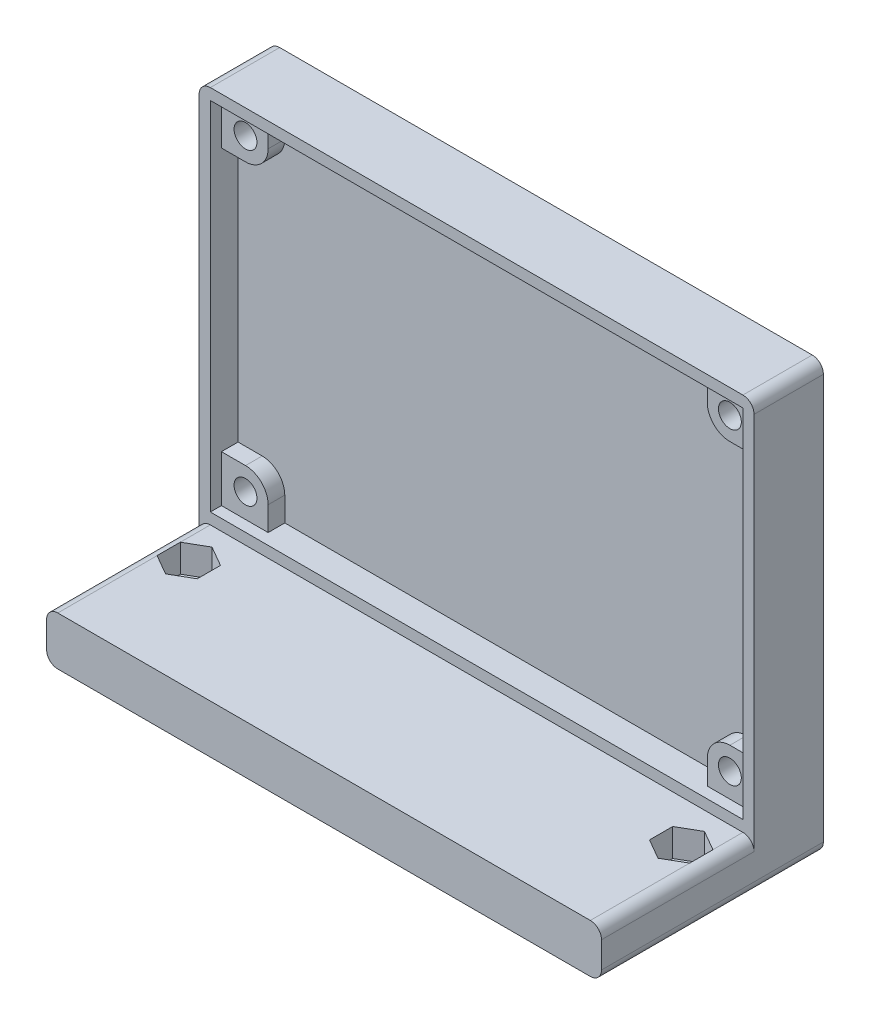
SolidWorks part; units mm, degrees
ref_plane "Front Plane" through (0, 0, 0) normal (0, 0, 1) x (1, 0, 0)
ref_plane "Top Plane" through (0, 0, 0) normal (0, 1, 0) x (1, 0, 0)
ref_plane "Right Plane" through (0, 0, 0) normal (1, 0, 0) x (0, 0, -1)
sketch "Sketch1" plane through (0, 0, 0) normal (0, 0, 1) x (1, 0, 0)
  line L23 (-40.01, -32.7) -> (-40.01, 25.7)
  line L25 (40.01, 25.7) -> (40.01, -32.7)
  line L30 (-38.4, -34.31) -> (38.4, -34.31)
  line L32 (-38.4, 27.31) -> (38.4, 27.31)
  circle A0 centre (-34.925, 22.225) radius 1.65
  circle A1 centre (-34.925, -22.225) radius 1.65
  circle A2 centre (34.925, 22.225) radius 1.65
  circle A3 centre (34.925, -22.225) radius 1.65
  arc A8 (-38.4, 27.31) -> (-40.01, 25.7) centre (-38.4, 25.7) ccw
  arc A9 (40.01, 25.7) -> (38.4, 27.31) centre (38.4, 25.7) ccw
  arc A10 (38.4, -34.31) -> (40.01, -32.7) centre (38.4, -32.7) ccw
  arc A11 (-40.01, -32.7) -> (-38.4, -34.31) centre (-38.4, -32.7) ccw
extrude "Boss-Extrude1" add sketch "Sketch1" along normal blind 32
sketch "Sketch4" plane through (0, 0, 32) normal (0, 0, 1) x (1, 0, 0)
  line L0 (-38.4, -27.31) -> (38.4, -27.31)
  line L1 (-40.01, -28.92) -> (-40.01, 25.7)
  line L2 (-38.4, 27.31) -> (38.4, 27.31)
  line L5 (40.01, -28.92) -> (40.01, 25.7)
  arc A0 (-38.4, 27.31) -> (-40.01, 25.7) centre (-38.4, 25.7) ccw
  arc A1 (40.01, 25.7) -> (38.4, 27.31) centre (38.4, 25.7) ccw
  arc A2 (-38.4, -27.31) -> (-40.01, -28.92) centre (-38.4, -28.92) ccw
  arc A3 (40.01, -28.92) -> (38.4, -27.31) centre (38.4, -28.92) ccw
extrude "Cut-Extrude3" cut sketch "Sketch4" against normal offset from surface (22 mm away) 10 up to face at (0, -3.5, 0)
sketch "Sketch2" plane through (0, 0, 32) normal (0, 0, 1) x (1, 0, 0)
  line L0 (-31.665, 25.7) -> (31.665, 25.7)
  line L1 (-38.4, 18.965) -> (-38.4, -18.965)
  line L2 (-31.665, -25.7) -> (31.665, -25.7)
  line L3 (38.4, 18.965) -> (38.4, -18.965)
  line L5 (-38.4, 18.965) -> (-34.925, 18.965)
  line L14 (-31.665, 25.7) -> (-31.665, 22.225)
  line L15 (31.665, 25.7) -> (31.665, 22.225)
  line L17 (34.925, 18.965) -> (38.4, 18.965)
  line L19 (38.4, -18.965) -> (34.925, -18.965)
  line L20 (31.665, -22.225) -> (31.665, -25.7)
  line L21 (-31.665, -22.225) -> (-31.665, -25.7)
  line L22 (-34.925, -18.965) -> (-38.4, -18.965)
  arc A0 (-34.925, 18.965) -> (-31.665, 22.225) centre (-34.925, 22.225) ccw
  arc A1 (34.925, 18.965) -> (31.665, 22.225) centre (34.925, 22.225) cw
  arc A2 (34.925, -18.965) -> (31.665, -22.225) centre (34.925, -22.225) ccw
  arc A3 (-34.925, -18.965) -> (-31.665, -22.225) centre (-34.925, -22.225) cw
extrude "Cut-Extrude1" cut sketch "Sketch2" against normal offset from surface (26 mm away) 6 up to face at (0, -3.5, 0)
sketch "Sketch3" plane through (0, 0, 32) normal (0, 0, 1) x (1, 0, 0)
  line L5 (-38.4, 25.7) -> (38.4, 25.7)
  line L6 (-38.4, 25.7) -> (-38.4, -25.7)
  line L7 (-38.4, -25.7) -> (38.4, -25.7)
  line L8 (38.4, 25.7) -> (38.4, -25.7)
extrude "Cut-Extrude2" cut sketch "Sketch3" against normal offset from surface (23.6 mm away) 1.6 up to face at (0, 0, 10) offset beyond the face yes
sketch "Sketch5" plane through (0, -27.31, 0) normal (0, 1, 0) x (1, 0, 0)
  circle A5 centre (-35.51, -16) radius 1.65
  circle A7 centre (35.51, -16) radius 1.65
extrude "Cut-Extrude4" cut sketch "Sketch5" against normal up to next
sketch "Sketch6" plane through (0, -27.31, 0) normal (0, 1, 0) x (1, 0, 0)
  line L6 (-35.51, -19.3486) -> (-32.61, -17.6743)
  line L7 (-32.61, -17.6743) -> (-32.61, -14.3257)
  line L8 (-32.61, -14.3257) -> (-35.51, -12.6514)
  line L9 (-35.51, -12.6514) -> (-38.41, -14.3257)
  line L10 (-38.41, -14.3257) -> (-38.41, -17.6743)
  line L11 (-38.41, -17.6743) -> (-35.51, -19.3486)
  line L12 (35.51, -19.3486) -> (38.41, -17.6743)
  line L13 (38.41, -17.6743) -> (38.41, -14.3257)
  line L14 (38.41, -14.3257) -> (35.51, -12.6514)
  line L15 (35.51, -12.6514) -> (32.61, -14.3257)
  line L16 (32.61, -14.3257) -> (32.61, -17.6743)
  line L17 (32.61, -17.6743) -> (35.51, -19.3486)
  circle A1 centre (-35.51, -16) radius 2.9 construction
  circle A2 centre (35.51, -16) radius 2.9 construction
extrude "Cut-Extrude5" cut sketch "Sketch6" against normal offset from surface (4 mm away) 3 up to face at (-35.51, -34.31, 17.65)
